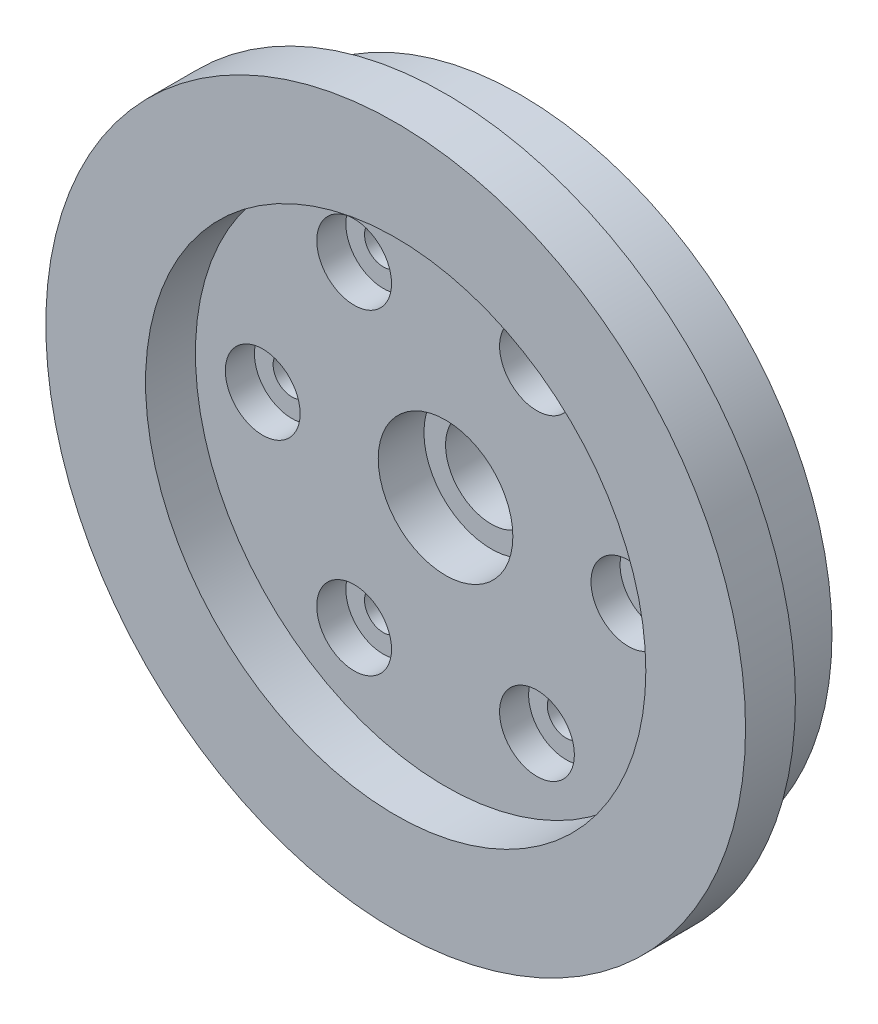
SolidWorks part; units mm, degrees
ref_plane "Plan de face" through (0, 0, 0) normal (0, 0, 1) x (1, 0, 0)
ref_plane "Plan de dessus" through (0, 0, 0) normal (0, 1, 0) x (1, 0, 0)
ref_plane "Plan de droite" through (0, 0, 0) normal (1, 0, 0) x (0, 0, -1)
sketch "Esquisse1" plane through (0, 0, 0) normal (0, 0, 1) x (1, 0, 0)
  line L0 (0, 0) -> (22, 0) construction
  line L1 (0, 0) -> (11, -19.0526) construction
  line L2 (0, 0) -> (-11, -19.0526) construction
  line L3 (0, 0) -> (-22, 0) construction
  line L4 (0, 0) -> (-11, 19.0526) construction
  line L5 (0, 0) -> (11, 19.0526) construction
  line L11 (23.5, -23.55) -> (-23.5, 23.55) construction
  line L12 (23.5, 23.55) -> (-23.5, -23.55) construction
  circle A0 centre (22, 0) radius 2.25
  circle A1 centre (11, -19.0526) radius 2.25
  circle A2 centre (-11, -19.0526) radius 2.25
  circle A3 centre (-22, 0) radius 2.25
  circle A4 centre (-11, 19.0526) radius 2.25
  circle A5 centre (11, 19.0526) radius 2.25
  circle A10 centre (0, 0) radius 30.1
  circle A11 centre (0, 0) radius 8.1
  point P17 (0, 0)
  dimension "D5" = 4.5
  dimension "D10" = 60.2
  dimension "D11" = 16.2
  dimension "D1" = 22
  dimension "D3" = 47
  dimension "D4" = 47.1
  dimension "D2" = 6
extrude "Boss.-Extru.1" add sketch "Esquisse1" along normal blind 10
sketch "Esquisse2" plane through (0, 0, 0) normal (0, 0, -1) x (-1, 0, 0)
  circle A0 centre (0, 0) radius 8.1
  circle A1 centre (0, 0) radius 5.5
  dimension "D1" = 11
extrude "Boss.-Extru.2" add sketch "Esquisse2" against normal blind 4.5
sketch "Esquisse3" plane through (0, 0, 10) normal (0, 0, 1) x (1, 0, 0)
  circle A0 centre (-11, 19.0526) radius 4.5
  circle A1 centre (11, 19.0526) radius 4.5
  circle A2 centre (22, 0) radius 4.5
  circle A3 centre (11, -19.0526) radius 4.5
  circle A4 centre (-11, -19.0526) radius 4.5
  circle A5 centre (-22, 0) radius 4.5
  point P15 (0, 0)
  dimension "D1" = 9
  dimension "D2" = 6
extrude "Enlèv. mat.-Extru.1" cut sketch "Esquisse3" against normal blind 3.5
sketch "Esquisse4" plane through (0, 0, 10) normal (0, 0, 1) x (1, 0, 0)
  line L0 (-42.1, 0) -> (-30.1, 0) construction
  circle A0 centre (0, 0) radius 42.1
  circle A1 centre (0, 0) radius 30.1
  circle A2 centre (0, 0) radius 30.1 construction
  point P8 (-40.1, 0)
  dimension "D1" = 12
extrude "Boss.-Extru.3" add sketch "Esquisse4" along normal blind 6
sketch "Esquisse6" plane through (0, 0, 10) normal (0, 0, -1) x (-1, 0, 0)
  circle A0 centre (0, 0) radius 37.5
  circle A1 centre (0, 0) radius 30.1
  dimension "D1" = 75
extrude "Boss.-Extru.4" add sketch "Esquisse6" along normal blind 9
